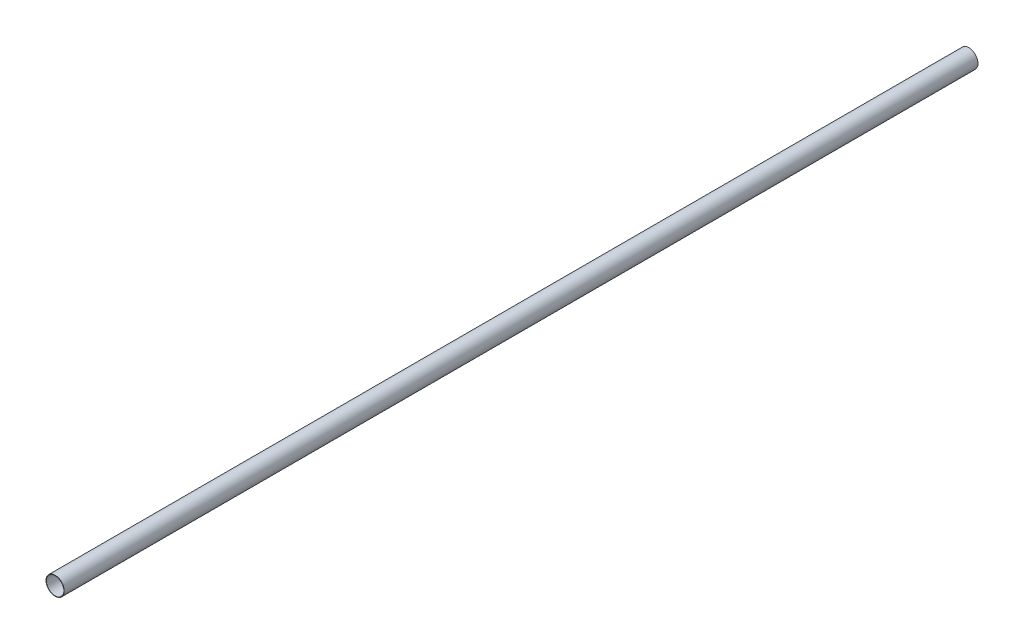
SolidWorks part; units mm, degrees
ref_plane "Front Plane" through (0, 0, 0) normal (0, 0, 1) x (1, 0, 0)
ref_plane "Top Plane" through (0, 0, 0) normal (0, 1, 0) x (1, 0, 0)
ref_plane "Right Plane" through (0, 0, 0) normal (1, 0, 0) x (0, 0, -1)
sketch "Sketch1" plane through (0, 0, 0) normal (0, 0, 1) x (1, 0, 0)
  circle A0 centre (0, 0) radius 15
  circle A1 centre (0, 0) radius 14.35
  dimension "D1" = 30
  dimension "D2" = 28.7
extrude "Boss-Extrude1" add sketch "Sketch1" along normal blind 1500
